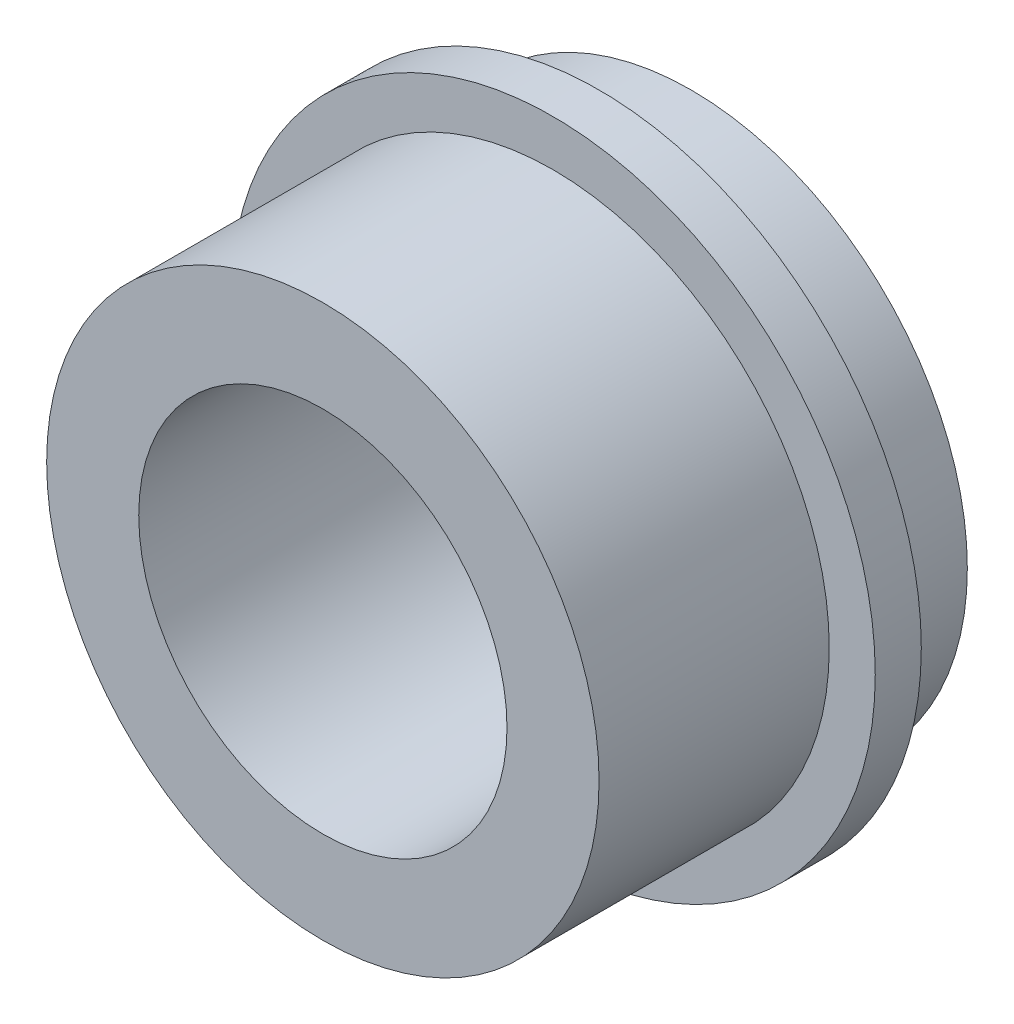
SolidWorks part; units mm, degrees
ref_plane "Front Plane" through (0, 0, 0) normal (0, 0, 1) x (1, 0, 0)
ref_plane "Top Plane" through (0, 0, 0) normal (0, 1, 0) x (1, 0, 0)
ref_plane "Right Plane" through (0, 0, 0) normal (1, 0, 0) x (0, 0, -1)
sketch "Sketch1" plane through (0, 0, 0) normal (0, 0, 1) x (1, 0, 0)
  circle A0 centre (0, 0) radius 4
  circle A1 centre (0, 0) radius 6
  dimension "D2" = 8
  dimension "D1" = 12
extrude "Boss-Extrude1" add sketch "Sketch1" along normal blind 8
sketch "Sketch2" plane through (0, 0, 8) normal (0, 0, 1) x (1, 0, 0)
  circle A0 centre (0, 0) radius 7
  circle A1 centre (0, 0) radius 4
  dimension "D1" = 14
extrude "Boss-Extrude2" add sketch "Sketch2" against normal blind 1 from offset 5
